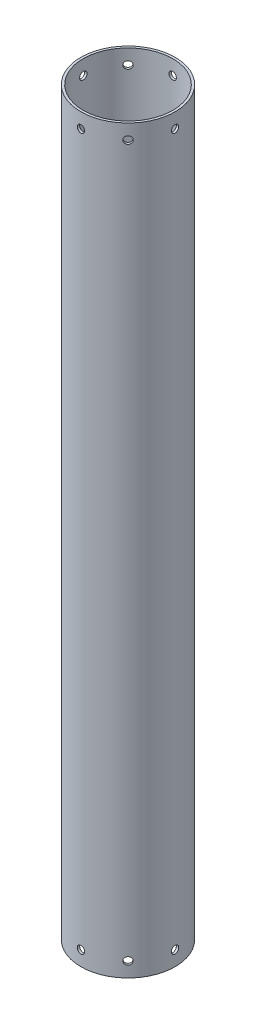
SolidWorks part; units mm, degrees
ref_plane "Front" through (0, 0, 0) normal (0, 0, 1) x (1, 0, 0)
ref_plane "Top" through (0, 0, 0) normal (0, 1, 0) x (1, 0, 0)
ref_plane "Right" through (0, 0, 0) normal (1, 0, 0) x (0, 0, -1)
sketch "Sketch1" plane through (0, 0, 0) normal (0, 1, 0) x (1, 0, 0)
  circle A0 centre (0, 0) radius 30.25
  circle A1 centre (0, 0) radius 31.85
  dimension "D1" = 60.5
  dimension "D2" = 1.6
extrude "Extrude1" add sketch "Sketch1" along normal blind 250
sketch "Sketch2" plane through (0, 0, 0) normal (1, 0, 0) x (0, 0, -1)
  circle A0 centre (0, 10) radius 2.5
  dimension "D1" = 5
  dimension "D2" = 10
extrude "Cut-Extrude1" cut sketch "Sketch2" against normal blind 500
ref_axis "Axis1" through (0, 250, 0) along (0, -1, 0)
pattern_circular "CirPattern1" count 8 over 360 about axis through (0, 250, 0) along (0, -1, 0) of "Cut-Extrude1"
mirror "Mirror1" about plane through (0, 250, 0) normal (0, 1, 0) of "CirPattern1", "Cut-Extrude1", "Extrude1"
